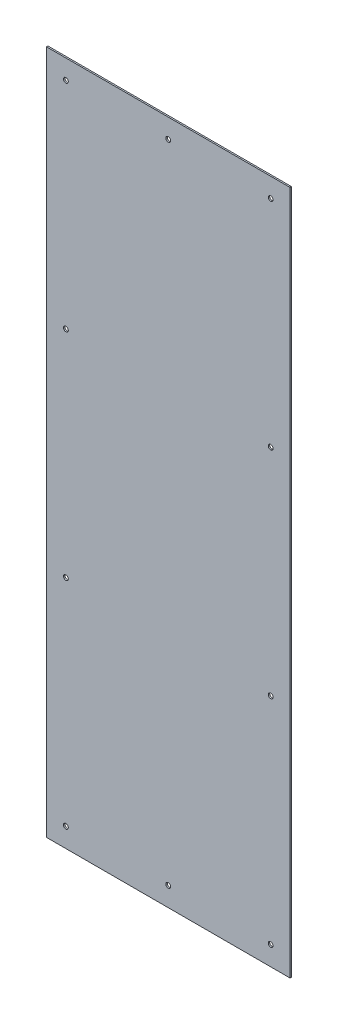
SolidWorks part; units mm, degrees
ref_plane "Alzado" through (0, 0, 0) normal (0, 0, 1) x (1, 0, 0)
ref_plane "Planta" through (0, 0, 0) normal (0, 1, 0) x (1, 0, 0)
ref_plane "Vista lateral" through (0, 0, 0) normal (1, 0, 0) x (0, 0, -1)
sketch "Croquis1" plane through (0, 0, 0) normal (0, 0, 1) x (1, 0, 0)
  line L1 (-160, 450) -> (160, 450)
  line L2 (-160, 450) -> (-160, -450)
  line L3 (-160, -450) -> (160, -450)
  line L4 (160, 450) -> (160, -450)
  line L5 (-160, 450) -> (160, -450) construction
  line L6 (-160, -450) -> (160, 450) construction
  point P0 (0, 0)
  dimension "D1" = 320
  dimension "D2" = 900
extrude "Saliente-Extruir1" add sketch "Croquis1" along normal blind 1.9
sketch "Croquis2" plane through (0, 0, 1.9) normal (0, 0, 1) x (1, 0, 0)
  line L0 (-160, 450) -> (-160, -450) construction
  line L1 (-134.6, -424.6) -> (134.6, -424.6) construction
  line L2 (-134.6, -424.6) -> (-134.6, 424.6) construction
  line L3 (-134.6, 424.6) -> (134.6, 424.6) construction
  line L4 (134.6, -424.6) -> (134.6, 424.6) construction
  line L5 (-134.6, -424.6) -> (134.6, 424.6) construction
  line L6 (-134.6, 424.6) -> (134.6, -424.6) construction
  line L7 (160, 450) -> (-160, 450) construction
  line L8 (-134.6, 0) -> (134.6, 0) construction
  line L9 (0, 0) -> (0, 424.6) construction
  line L10 (-134.6, 424.6) -> (-134.6, 141.54) construction
  line L11 (-134.6, 141.54) -> (-118.744, 141.54) construction
  line L12 (-134.6, 141.54) -> (-134.6, -141.52) construction
  circle A0 centre (-134.6, 424.6) radius 3.175
  circle A1 centre (134.6, 424.6) radius 3.175
  circle A2 centre (134.6, -424.6) radius 3.175
  circle A3 centre (-134.6, -424.6) radius 3.175
  circle A4 centre (-134.6, 141.54) radius 3.175
  circle A5 centre (-134.6, -141.52) radius 3.175
  circle A6 centre (134.6, 141.54) radius 3.175
  circle A7 centre (134.6, -141.52) radius 3.175
  circle A8 centre (0, 424.6) radius 3.175
  circle A9 centre (0, -424.6) radius 3.175
  point P0 (0, 0)
  point P8 (0, 424.6)
  dimension "D3" = 6.35
  dimension "D5" = 6.35
  dimension "D7" = 6.35
  dimension "D8" = 6.35
  dimension "D9" = 6.35
  dimension "D1" = 25.4
  dimension "D2" = 25.4
  dimension "D4" = 283.06
  dimension "D6" = 283.06
extrude "Cortar-Extruir1" cut sketch "Croquis2" against normal blind 10
